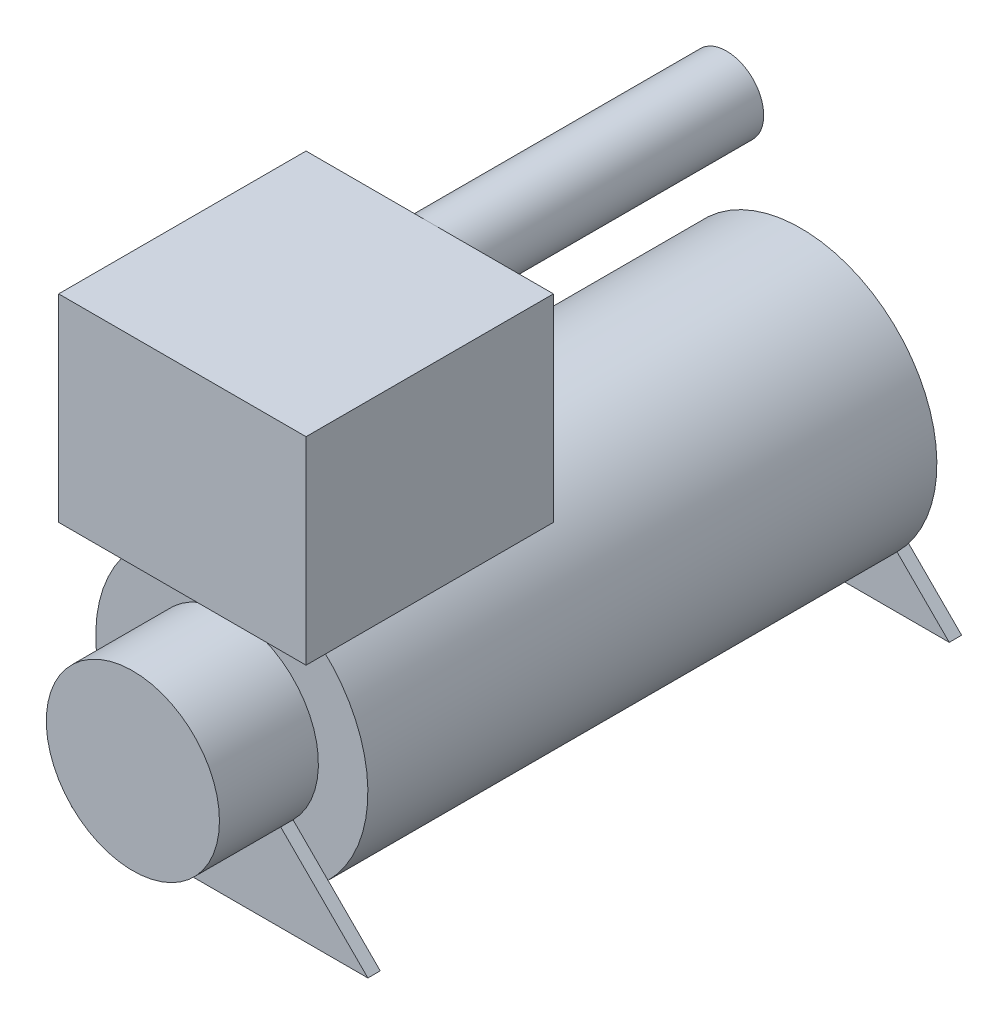
SolidWorks part; units mm, degrees
material "Air Compressor"
ref_plane "Front Plane" through (0, 0, 0) normal (0, 0, 1) x (1, 0, 0)
ref_plane "Top Plane" through (0, 0, 0) normal (0, 1, 0) x (1, 0, 0)
ref_plane "Right Plane" through (0, 0, 0) normal (1, 0, 0) x (0, 0, -1)
sketch "Sketch1" plane through (0, 0, 0) normal (0, 0, 1) x (1, 0, 0)
  circle A0 centre (0, 0) radius 34.925
  dimension "D1" = 69.85
extrude "Boss-Extrude1" add sketch "Sketch1" along normal blind 146.05
sketch "Sketch2" plane through (0, 0, 146.05) normal (0, 0, 1) x (1, 0, 0)
  line L0 (0, 0) -> (-38.1, -38.1)
  line L1 (38.1, -38.1) -> (0, 0)
  line L2 (38.1, -38.1) -> (-38.1, -38.1)
  point P4 (0, -38.1)
  dimension "D1" = 38.1
  dimension "D2" = 76.2
extrude "Boss-Extrude2" add sketch "Sketch2" along normal blind 3.175
pattern_linear "LPattern1" count 2 spacing 149.225 along (0, 0, -1) of "Boss-Extrude2"
sketch "Sketch4" plane through (0, 0, 146.05) normal (0, 0, 1) x (1, 0, 0)
  circle A0 centre (0, 0) radius 22.225
  dimension "D1" = 44.45
extrude "Boss-Extrude3" add sketch "Sketch4" along normal blind 25.4
ref_plane "Plane1" through (0, 33.02, 0) normal (0, 1, 0) x (1, 0, 0)
sketch "Sketch5" plane through (0, 33.02, 0) normal (0, 1, 0) x (1, 0, 0)
  line L0 (-22.225, -171.45) -> (22.225, -171.45) construction
  line L1 (-31.75, -95.25) -> (31.75, -95.25)
  line L2 (-31.75, -95.25) -> (-31.75, -158.75)
  line L3 (-31.75, -158.75) -> (31.75, -158.75)
  line L4 (31.75, -95.25) -> (31.75, -158.75)
  dimension "D1" = 63.5
  dimension "D2" = 63.5
  dimension "D3" = 31.75
  dimension "D4" = 12.7
extrude "Boss-Extrude4" add sketch "Sketch5" along normal blind 50.8
sketch "Sketch6" plane through (0, 0, 95.25) normal (0, 0, -1) x (-1, 0, 0)
  line L0 (-31.75, 83.82) -> (31.75, 83.82) construction
  circle A0 centre (0, 74.295) radius 9.525
  dimension "D1" = 19.05
  dimension "D2" = 9.525
extrude "Boss-Extrude5" add sketch "Sketch6" along normal blind 76.2
